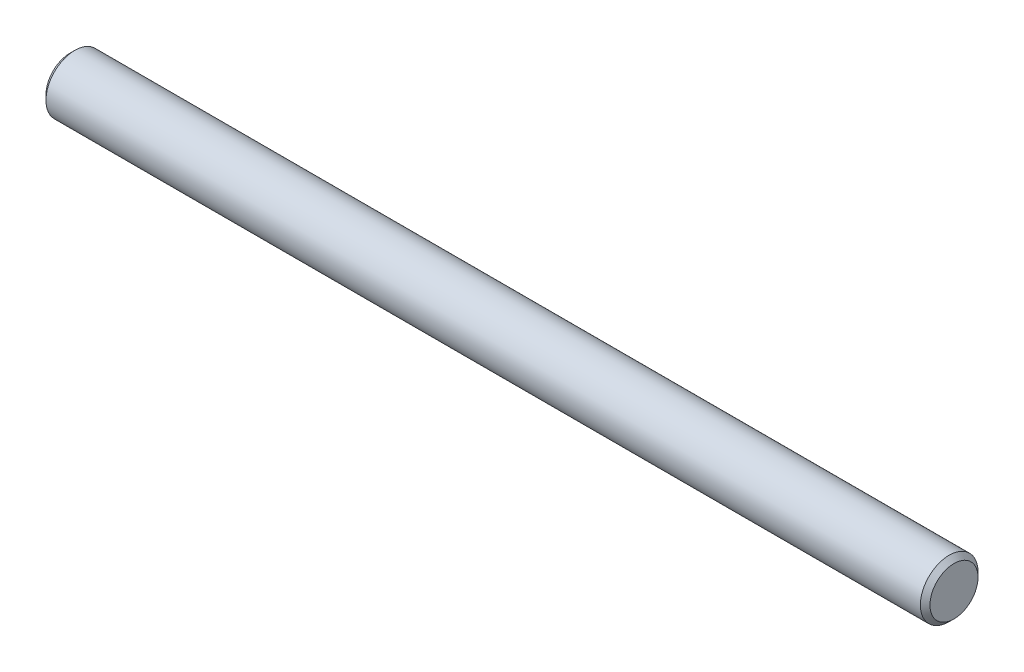
SolidWorks part; units mm, degrees
material "Chrome Stainless Steel"
ref_plane "Front Plane" through (0, 0, 0) normal (0, 0, 1) x (1, 0, 0)
ref_plane "Top Plane" through (0, 0, 0) normal (0, 1, 0) x (1, 0, 0)
ref_plane "Right Plane" through (0, 0, 0) normal (1, 0, 0) x (0, 0, -1)
sketch "Sketch1" plane through (0, 0, 0) normal (1, 0, 0) x (0, 0, -1)
  circle A0 centre (0, 0) radius 6
  dimension "D1" = 12
extrude "Boss-Extrude1" add sketch "Sketch1" along normal blind 184
chamfer "Chamfer1" distance 1 angle 45 2 edges at (184, 0, -6) (0, 0, -6)
